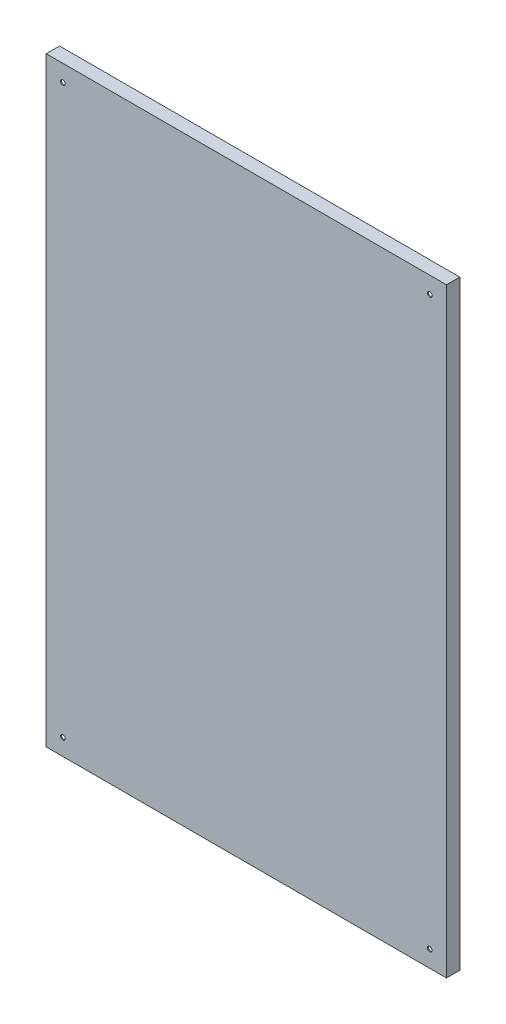
SolidWorks part; units mm, degrees
material "冷板"
ref_plane "前视基准面" through (0, 0, 0) normal (0, 0, 1) x (1, 0, 0)
ref_plane "上视基准面" through (0, 0, 0) normal (0, 1, 0) x (1, 0, 0)
ref_plane "右视基准面" through (0, 0, 0) normal (1, 0, 0) x (0, 0, -1)
sketch "草图1" plane through (0, 0, 0) normal (0, 0, 1) x (1, 0, 0)
  line L0 (0, 491.1739) -> (0, 0) construction
  line L1 (0, 0) -> (421.6954, 0) construction
  line L3 (-300, 450) -> (300, 450)
  line L4 (-300, 450) -> (-300, -450)
  line L5 (-300, -450) -> (300, -450)
  line L6 (300, 450) -> (300, -450)
  dimension "D1" = 600
  dimension "D2" = 900
extrude "凸台-拉伸1" add sketch "草图1" along normal blind 1.5
sketch "草图2" plane through (0, 0, 0) normal (0, 0, -1) x (-1, 0, 0)
  line L0 (0, 515.3034) -> (0, 0) construction
  line L1 (0, 0) -> (417.7311, 0) construction
  line L2 (298.5, -448.5) -> (298.5, 448.5)
  line L3 (298.5, 448.5) -> (-298.5, 448.5)
  line L4 (-298.5, 448.5) -> (-298.5, -448.5)
  line L5 (-298.5, -448.5) -> (298.5, -448.5)
  line L6 (300, -450) -> (300, 450)
  line L7 (300, 450) -> (-300, 450)
  line L8 (-300, 450) -> (-300, -450)
  line L9 (-300, -450) -> (300, -450)
  line L10 (300, -450) -> (300, 450)
  line L11 (300, 450) -> (-300, 450)
  line L12 (-300, 450) -> (-300, -450)
  line L13 (-300, -450) -> (300, -450)
  dimension "D1" = 0
  dimension "D2" = 1.5
extrude "凸台-拉伸2" add sketch "草图2" along normal offset from surface (18.5 mm away) 20 up to face at (0, 0, 1.5)
sketch "草图4" plane through (0, 0, 1.5) normal (0, 0, 1) x (1, 0, 0)
  line L1 (275, 425) -> (-275, 425) construction
  line L3 (275, 425) -> (275, -425) construction
  line L4 (275, -425) -> (-275, -425) construction
  line L5 (-275, 425) -> (-275, -425) construction
  line L6 (275, 425) -> (-275, -425) construction
  line L7 (275, -425) -> (-275, 425) construction
  circle A0 centre (-275, 425) radius 3.5
  circle A1 centre (275, 425) radius 3.5
  circle A2 centre (-275, -425) radius 3.5
  circle A3 centre (275, -425) radius 3.5
  point P0 (0, 0)
  dimension "D1" = 7
  dimension "D2" = 550
  dimension "D3" = 850
extrude "切除-拉伸1" cut sketch "草图4" against normal blind 10
